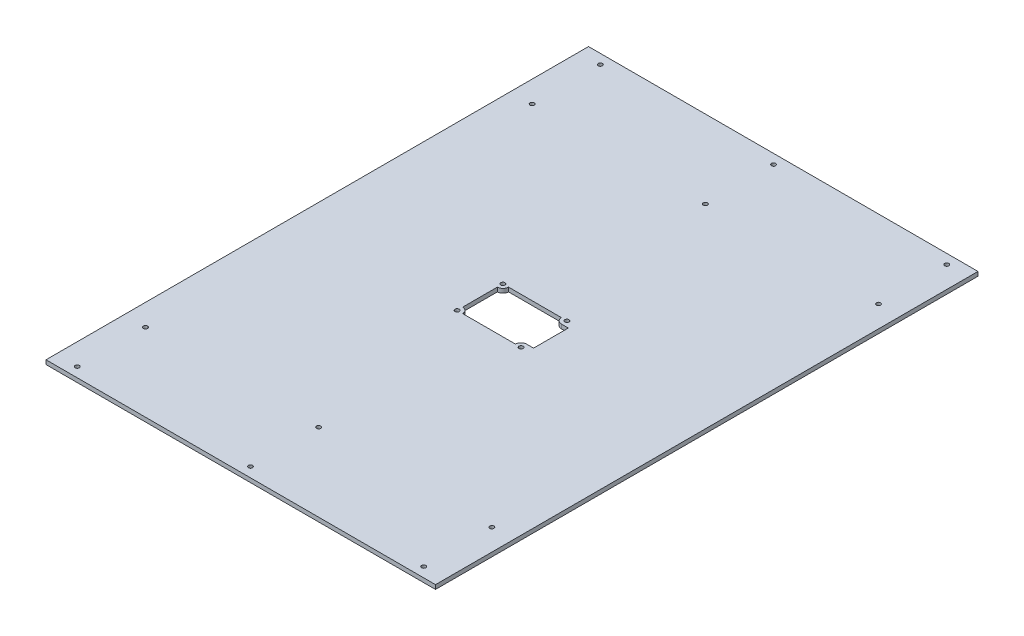
SolidWorks part; units mm, degrees
ref_plane "前视基准面" through (0, 0, 0) normal (0, 0, 1) x (1, 0, 0)
ref_plane "上视基准面" through (0, 0, 0) normal (0, 1, 0) x (1, 0, 0)
ref_plane "右视基准面" through (0, 0, 0) normal (1, 0, 0) x (0, 0, -1)
sketch "草图1" plane through (0, 0, 0) normal (0, 1, 0) x (1, 0, 0)
  line L1 (0, 0) -> (280, 0)
  line L2 (0, 0) -> (0, 390)
  line L3 (0, 390) -> (280, 390)
  line L4 (280, 0) -> (280, 390)
  dimension "D1" = 280
  dimension "D2" = 390
extrude "凸台-拉伸1" add sketch "草图1" along normal blind 3
sketch "草图2" plane through (0, 3, 0) normal (0, 1, 0) x (1, 0, 0)
  line L0 (140, 390) -> (140, 0) construction
  line L1 (280, 390) -> (0, 390) construction
  line L2 (0, 0) -> (280, 0) construction
  line L3 (0, 195) -> (280, 195) construction
  line L4 (0, 390) -> (0, 0) construction
  line L5 (280, 0) -> (280, 390) construction
  circle A0 centre (140, 383) radius 1.5
  circle A1 centre (140, 334) radius 1.5
  circle A2 centre (264.5, 383) radius 1.5
  circle A3 centre (264.5, 334) radius 1.5
  circle A4 centre (15.5, 383) radius 1.5
  circle A5 centre (15.5, 334) radius 1.5
  circle A6 centre (264.5, 56) radius 1.5
  circle A7 centre (264.5, 7) radius 1.5
  circle A8 centre (140, 7) radius 1.5
  circle A9 centre (140, 56) radius 1.5
  circle A10 centre (15.5, 56) radius 1.5
  circle A11 centre (15.5, 7) radius 1.5
  dimension "D3" = 3
  dimension "D1" = 7
  dimension "D2" = 124.5
  dimension "D4" = 49
extrude "切除-拉伸1" cut sketch "草图2" against normal through all
sketch "草图3" plane through (0, 3, 0) normal (0, 1, 0) x (1, 0, 0)
  line L0 (140, 390) -> (140, 0) construction
  line L1 (280, 390) -> (0, 390) construction
  line L2 (0, 0) -> (280, 0) construction
  line L3 (0, 195) -> (280, 195) construction
  line L5 (0, 390) -> (0, 0) construction
  line L6 (280, 0) -> (280, 390) construction
  circle A0 centre (117, 211.5) radius 1.5
  circle A1 centre (163, 211.5) radius 1.5
  circle A2 centre (163, 178.5) radius 1.5
  circle A3 centre (117, 178.5) radius 1.5
  dimension "D5" = 3
  dimension "D1" = 46
  dimension "D2" = 33
  dimension "D3" = 23
  dimension "D4" = 16.5
extrude "切除-拉伸2" cut sketch "草图3" against normal through all
sketch "草图6" plane through (0, 3, 0) normal (0, 1, 0) x (1, 0, 0)
  line L0 (121, 211.5) -> (159, 211.5)
  line L1 (163, 207.5) -> (163, 182.5)
  line L2 (159, 178.5) -> (121, 178.5)
  line L3 (117, 182.5) -> (117, 207.5)
  arc A0 (117, 207.5) -> (121, 211.5) centre (117, 211.5) ccw
  arc A1 (159, 211.5) -> (163, 207.5) centre (163, 211.5) ccw
  arc A2 (163, 182.5) -> (159, 178.5) centre (163, 178.5) ccw
  arc A3 (121, 178.5) -> (117, 182.5) centre (117, 178.5) ccw
  dimension "D1" = 8
extrude "切除-拉伸5" cut sketch "草图6" against normal through all
sketch "草图7" plane through (0, 3, 0) normal (0, 1, 0) x (1, 0, 0)
  line L1 (163, 207.5) -> (168, 207.5)
  line L2 (163, 207.5) -> (163, 182.5)
  line L3 (163, 182.5) -> (168, 182.5)
  line L4 (168, 207.5) -> (168, 182.5)
  dimension "D1" = 5
extrude "切除-拉伸6" cut sketch "草图7" against normal through all
